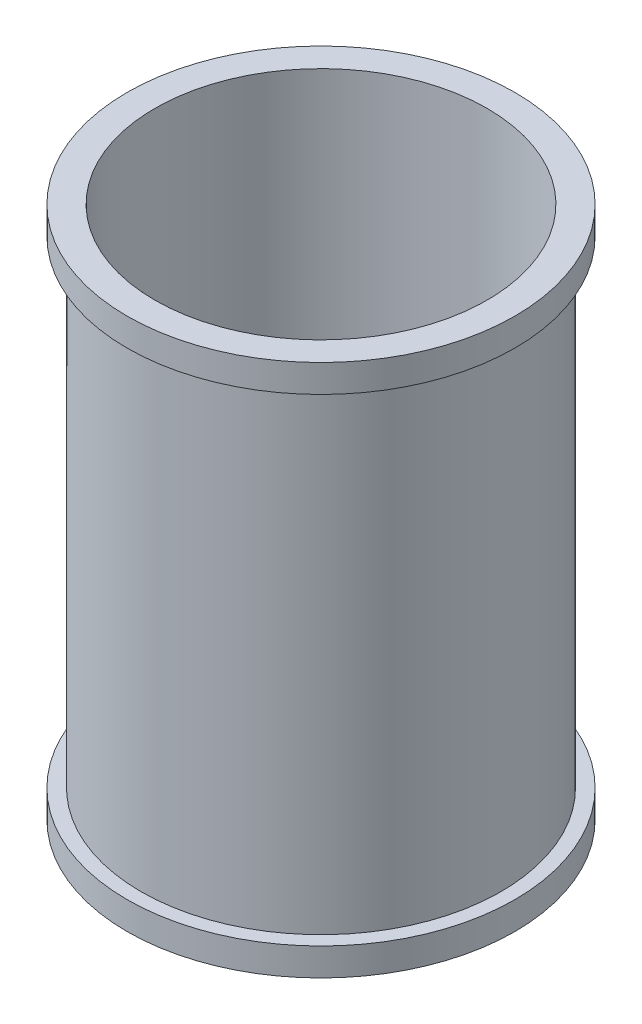
SolidWorks part; units mm, degrees
ref_plane "Front Plane" through (0, 0, 0) normal (0, 0, 1) x (1, 0, 0)
ref_plane "Top Plane" through (0, 0, 0) normal (0, 1, 0) x (1, 0, 0)
ref_plane "Right Plane" through (0, 0, 0) normal (1, 0, 0) x (0, 0, -1)
sketch "Sketch1" plane through (0, 0, 0) normal (0, 1, 0) x (1, 0, 0)
  circle A0 centre (0, 0) radius 76.2
  circle A1 centre (0, 0) radius 88.9
extrude "Boss-Extrude1" add sketch "Sketch1" along normal blind 12.7
sketch "Sketch2" plane through (0, 12.7, 0) normal (0, 1, 0) x (1, 0, 0)
  circle A0 centre (0, 0) radius 76.2
  circle A1 centre (0, 0) radius 82.55
extrude "Boss-Extrude2" add sketch "Sketch2" along normal blind 219.075
sketch "Sketch3" plane through (0, 231.775, 0) normal (0, 1, 0) x (1, 0, 0)
  circle A0 centre (0, 0) radius 76.2
  circle A1 centre (0, 0) radius 88.9
extrude "Boss-Extrude3" add sketch "Sketch3" along normal blind 12.7
